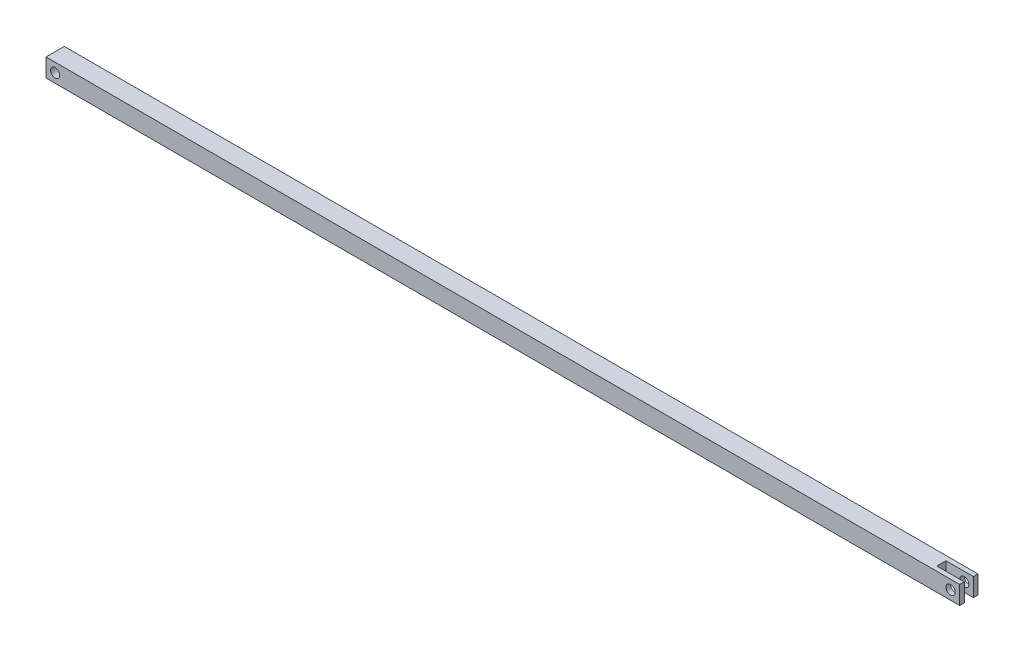
SolidWorks part; units mm, degrees
ref_plane "Спереди" through (0, 0, 0) normal (0, 0, 1) x (1, 0, 0)
ref_plane "Сверху" through (0, 0, 0) normal (0, 1, 0) x (1, 0, 0)
ref_plane "Справа" through (0, 0, 0) normal (1, 0, 0) x (0, 0, -1)
sketch "Эскиз1" plane through (0, 0, 0) normal (0, 0, 1) x (1, 0, 0)
  line L0 (0, 0) -> (0, -10) construction
  line L1 (-500, -10) -> (500, -10)
  line L2 (-500, -10) -> (-500, 10)
  line L3 (-500, 10) -> (500, 10)
  line L4 (500, -10) -> (500, 10)
  line L5 (-500, -10) -> (500, 10) construction
  line L6 (-500, 10) -> (500, -10) construction
  circle A0 centre (-490, 0) radius 5
  circle A1 centre (490, 0) radius 5
  point P0 (0, 0)
  point P10 (0, 0)
  dimension "D3" = 10
  dimension "D1" = 20
  dimension "D2" = 1000
  dimension "D4" = 10
  dimension "D5" = 10
extrude "Бобышка-Вытянуть1" add sketch "Эскиз1" along normal blind 20
sketch "Эскиз2" plane through (0, 10, 0) normal (0, 1, 0) x (1, 0, 0)
  line L0 (500, -20) -> (500, 0) construction
  line L1 (500, -5) -> (470, -5)
  line L2 (470, -5) -> (470, -15)
  line L3 (470, -15) -> (500, -15)
  line L5 (500, 0) -> (-500, 0) construction
  dimension "D1" = 10
  dimension "D2" = 5
  dimension "D3" = 30
extrude "Вырез-Вытянуть1" cut sketch "Эскиз2" against normal blind 20 and the other way through all
